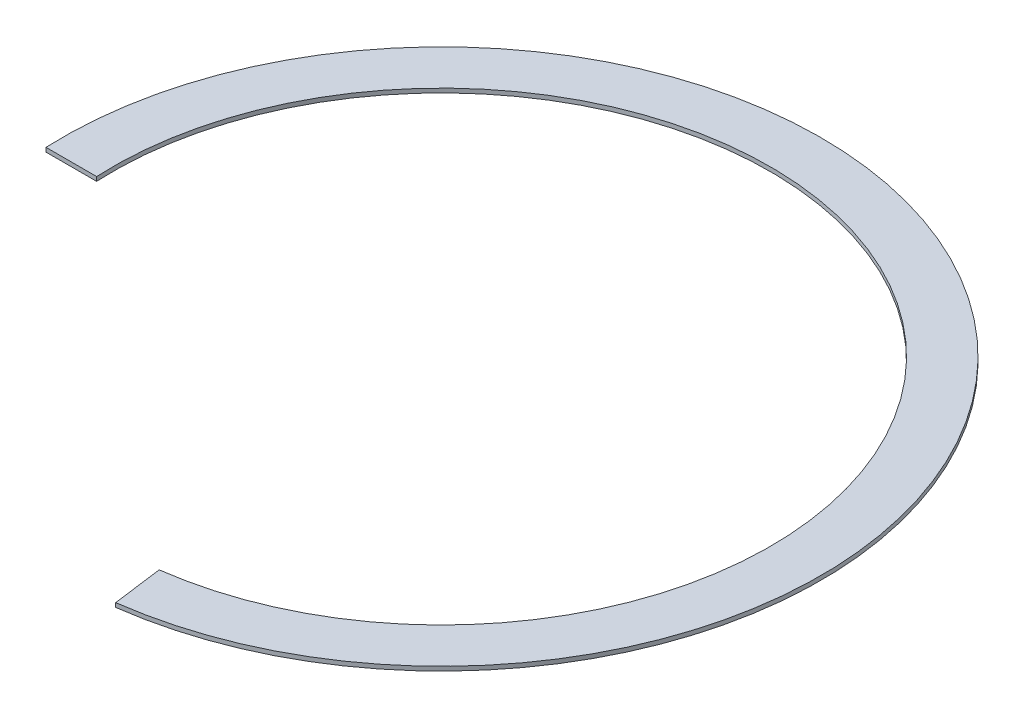
SolidWorks part; units mm, degrees
material "6061-T6"
ref_plane "Front" through (0, 0, 0) normal (0, 0, 1) x (1, 0, 0)
ref_plane "Top" through (0, 0, 0) normal (0, 1, 0) x (1, 0, 0)
ref_plane "Right" through (0, 0, 0) normal (1, 0, 0) x (0, 0, -1)
sketch "Sketch1" plane through (0, 0, 0) normal (0, 1, 0) x (1, 0, 0)
  line L0 (-63.4294, -2.7728) -> (-54.9601, -2.7728)
  line L3 (8.3971, -62.9323) -> (7.2782, -54.5466)
  line L4 (-54.9601, -2.7728) -> (0, 0) construction
  line L5 (0, 0) -> (7.2782, -54.5466) construction
  arc A0 (7.2782, -54.5466) -> (-54.9601, -2.7728) centre (0, 0) ccw
  arc A1 (8.3971, -62.9323) -> (-63.4294, -2.7728) centre (0, 0) ccw
  dimension "D2" = 8.4693
  dimension "D3" = 8.46
  dimension "D4" = 265.288
  dimension "D6" = 55.03
  dimension "D1" = 63.49
extrude "Boss-Extrude1" add sketch "Sketch1" along normal blind 0.7
